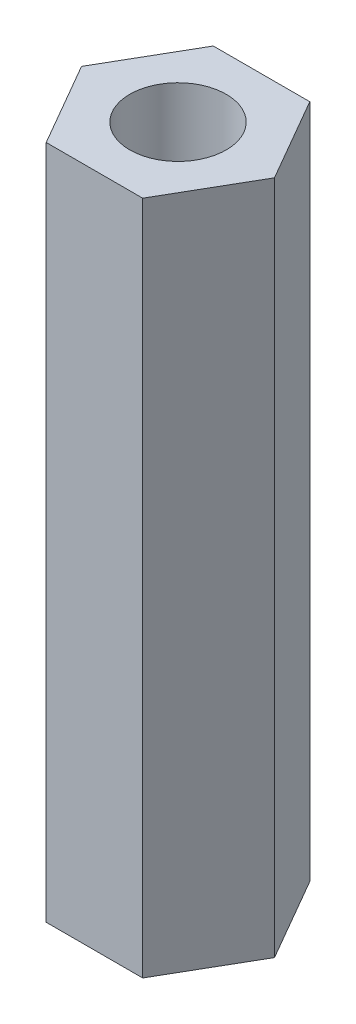
SolidWorks part; units mm, degrees
ref_plane "Front Plane" through (0, 0, 0) normal (0, 0, 1) x (1, 0, 0)
ref_plane "Top Plane" through (0, 0, 0) normal (0, 1, 0) x (1, 0, 0)
ref_plane "Right Plane" through (0, 0, 0) normal (1, 0, 0) x (0, 0, -1)
sketch "Sketch1" plane through (0, 0, 0) normal (0, 1, 0) x (1, 0, 0)
  line L1 (-2.5, -4.3301) -> (2.5, -4.3301)
  line L2 (2.5, -4.3301) -> (5, 0)
  line L3 (5, 0) -> (2.5, 4.3301)
  line L4 (2.5, 4.3301) -> (-2.5, 4.3301)
  line L5 (-2.5, 4.3301) -> (-5, 0)
  line L6 (-5, 0) -> (-2.5, -4.3301)
  circle A0 centre (0, 0) radius 4.3301 construction
  circle A1 centre (0, 0) radius 2.5
  dimension "D1" = 5
  dimension "D2" = 5
extrude "Boss-Extrude1" add sketch "Sketch1" along normal blind 35
